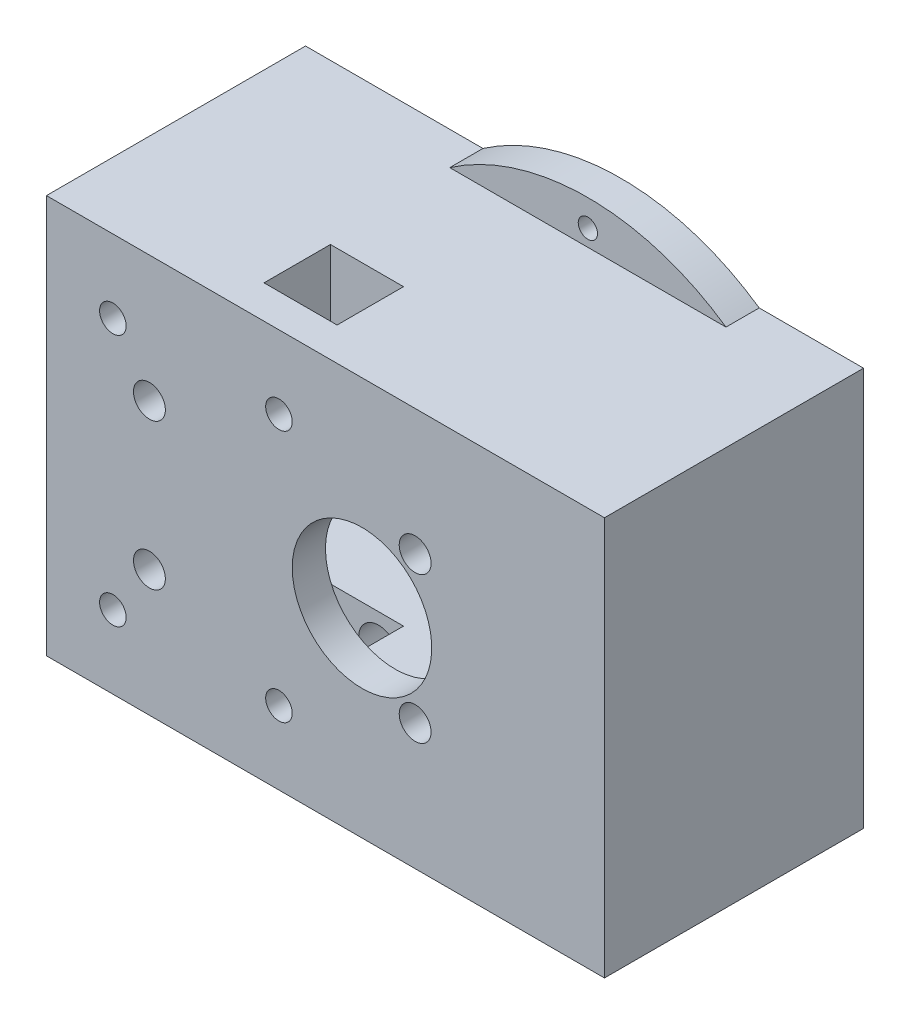
SolidWorks part; units mm, degrees
ref_plane "前视基准面" through (0, 0, 0) normal (0, 0, 1) x (1, 0, 0)
ref_plane "上视基准面" through (0, 0, 0) normal (0, 1, 0) x (1, 0, 0)
ref_plane "右视基准面" through (0, 0, 0) normal (1, 0, 0) x (0, 0, -1)
sketch "草图1" plane through (0, 0, 0) normal (0, 0, 1) x (1, 0, 0)
  line L1 (-33.4499, 20.5621) -> (50.5501, 20.5621)
  line L2 (-33.4499, 20.5621) -> (-33.4499, -39.4379)
  line L3 (-33.4499, -39.4379) -> (50.5501, -39.4379)
  line L4 (50.5501, 20.5621) -> (50.5501, -39.4379)
  dimension "D1" = 84
  dimension "D2" = 60
extrude "凸台-拉伸1" add sketch "草图1" along normal blind 39
sketch "草图3" plane through (0, 0, 0) normal (0, 0, -1) x (-1, 0, 0)
  line L1 (-50.5501, -39.4379) -> (-50.5501, 20.5621) construction
  line L2 (33.4499, -39.4379) -> (-50.5501, -39.4379) construction
  circle A0 centre (-14.0501, -9.4379) radius 36.5
  point P2 (-21.5499, -29.1391)
  dimension "D1" = 36.5
  dimension "D2" = 30
extrude "凸台-拉伸2" add sketch "草图3" against normal blind 5
sketch "草图4" plane through (0, 0, 0) normal (0, 0, -1) x (-1, 0, 0)
  line L0 (-50.5501, -39.4379) -> (-50.5501, 20.5621) construction
  line L1 (-34.8408, -39.4379) -> (-50.5501, -39.4379) construction
  circle A0 centre (-46.5501, -9.4379) radius 1.45
  dimension "D1" = 2.9
  dimension "D2" = 4
  dimension "D3" = 30
extrude "切除-拉伸2" cut sketch "草图4" against normal blind 5
pattern_circular "阵列(圆周)1" count 8 over 360 about axis through (14.0501, -9.4379, 0) along (0, 0, 1) of "切除-拉伸2"
sketch "草图2" plane through (0, 0, 0) normal (0, 0, -1) x (-1, 0, 0)
  line L0 (33.4499, 20.5621) -> (33.4499, -39.4379) construction
  line L1 (33.4499, 4.8121) -> (-25.3001, 4.8121)
  line L2 (33.4499, 4.8121) -> (33.4499, -23.6879)
  line L3 (33.4499, -23.6879) -> (-25.3001, -23.6879)
  line L4 (-25.3001, 4.8121) -> (-25.3001, -23.6879)
  line L5 (-50.5501, 20.5621) -> (-34.8408, 20.5621) construction
  line L6 (33.4499, -39.4379) -> (6.7405, -39.4379) construction
  dimension "D1" = 58.75
  dimension "D2" = 15.75
  dimension "D3" = 15.75
extrude "切除-拉伸1" cut sketch "草图2" against normal blind 34
sketch "草图6" plane through (0, 0, 34) normal (0, 0, -1) x (-1, 0, 0)
  line L1 (-25.3001, -23.6879) -> (33.4499, -23.6879) construction
  line L2 (33.4499, -23.6879) -> (33.4499, 4.8121) construction
  line L3 (33.4499, 4.8121) -> (-25.3001, 4.8121) construction
  line L4 (-25.3001, -23.6879) -> (33.4499, -23.6879) construction
  line L5 (33.4499, 4.8121) -> (-25.3001, 4.8121) construction
  circle A0 centre (-14.0501, -9.4379) radius 10.5
  circle A1 centre (-22.0501, 1.5621) radius 2.4
  circle A2 centre (-22.0501, -20.4379) radius 2.4
  circle A3 centre (17.9499, -20.4379) radius 2.4
  circle A4 centre (17.9499, 1.5621) radius 2.4
  dimension "D1" = 14.25
  dimension "D2" = 47.5
  dimension "D3" = 3.25
  dimension "D4" = 55.5
  dimension "D5" = 3.25
  dimension "D6" = 55.5
  dimension "D7" = 3.25
  dimension "D8" = 15.5
  dimension "D9" = 3.25
  dimension "D10" = 15.5
extrude "切除-拉伸3" cut sketch "草图6" against normal blind 5
sketch "草图7" plane through (0, 0, 39) normal (0, 0, 1) x (1, 0, 0)
  line L0 (50.5501, 20.5621) -> (-33.4499, 20.5621) construction
  line L1 (-33.4499, 20.5621) -> (-33.4499, -39.4379) construction
  line L2 (-33.4499, -39.4379) -> (50.5501, -39.4379) construction
  circle A0 centre (-23.4499, 9.5621) radius 2
  circle A1 centre (-23.4499, -28.4379) radius 2
  circle A2 centre (1.5501, 9.5621) radius 2
  circle A3 centre (1.5501, -28.4379) radius 2
  dimension "D1" = 11
  dimension "D2" = 10
  dimension "D3" = 10
  dimension "D4" = 11
  dimension "D5" = 25
  dimension "D6" = 25
extrude "切除-拉伸4" cut sketch "草图7" against normal blind 40
sketch "草图8" plane through (0, 0, 0) normal (0, 0, -1) x (-1, 0, 0)
  circle A0 centre (-1.5501, 9.5621) radius 3
  circle A1 centre (23.4499, 9.5621) radius 3
  circle A2 centre (-1.5501, -28.4379) radius 3
  circle A3 centre (23.4499, -28.4379) radius 3
extrude "切除-拉伸5" cut sketch "草图8" against normal blind 34
sketch "草图9" plane through (0, -39.4379, 0) normal (0, -1, 0) x (-1, 0, 0)
  line L0 (-50.5501, -39) -> (-50.5501, 0) construction
  line L1 (5.6999, -34) -> (-5.3001, -34)
  line L2 (5.6999, -34) -> (5.6999, -24)
  line L3 (5.6999, -24) -> (-5.3001, -24)
  line L4 (-5.3001, -34) -> (-5.3001, -24)
  line L5 (33.4499, -39) -> (-50.5501, -39) construction
  dimension "D1" = 11
  dimension "D2" = 10
  dimension "D3" = 45.25
  dimension "D4" = 5
extrude "切除-拉伸6" cut sketch "草图9" against normal blind 100
